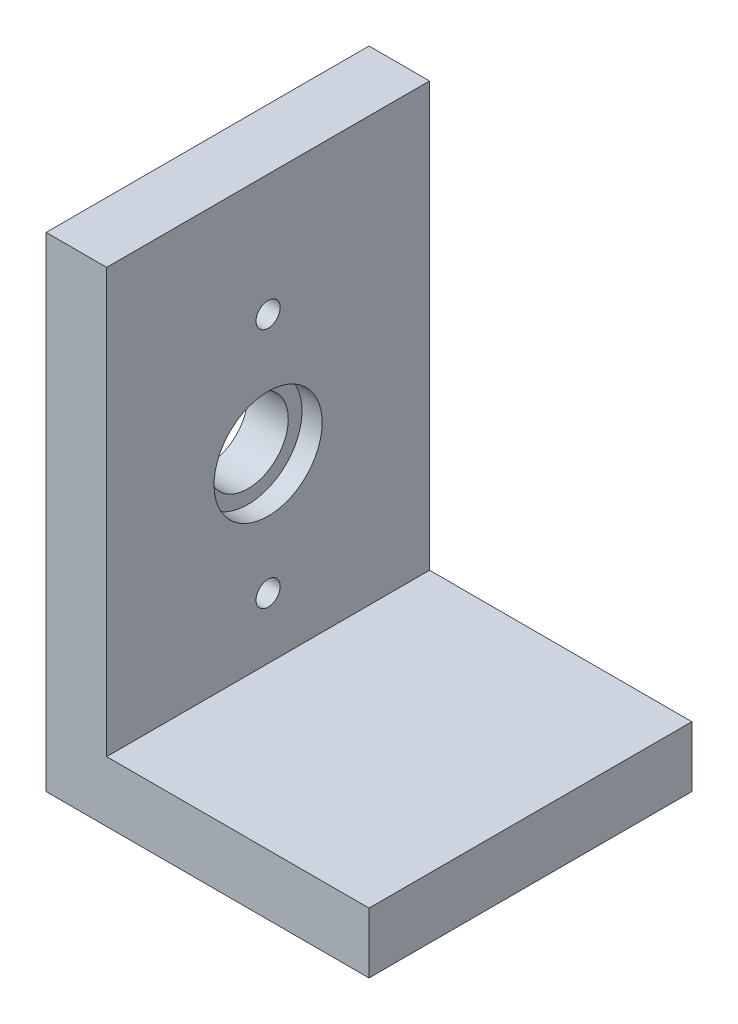
SolidWorks part; units mm, degrees
material "6061-T6 (SS)"
ref_plane "Front Plane" through (0, 0, 0) normal (0, 0, 1) x (1, 0, 0)
ref_plane "Top Plane" through (0, 0, 0) normal (0, 1, 0) x (1, 0, 0)
ref_plane "Right Plane" through (0, 0, 0) normal (1, 0, 0) x (0, 0, -1)
sketch "Sketch2" plane through (0, 0, 0) normal (0, 0, 1) x (1, 0, 0)
  line L0 (0, 0) -> (0, 76.2)
  line L1 (0, 76.2) -> (9.525, 76.2)
  line L2 (9.525, 76.2) -> (9.525, 9.525)
  line L3 (9.525, 9.525) -> (50.8, 9.525)
  line L4 (50.8, 9.525) -> (50.8, 0)
  line L5 (50.8, 0) -> (0, 0)
  dimension "D1" = 50.8
  dimension "D2" = 76.2
  dimension "D3" = 9.525
  dimension "D4" = 9.525
extrude "Boss-Extrude1" add sketch "Sketch2" along normal mid plane 50.8
sketch "Sketch5" plane through (9.525, 0, 0) normal (1, 0, 0) x (0, 0, -1)
  circle A0 centre (0, 38.1) radius 8.509
  point P2 (0, 0)
  dimension "D1" = 17.018
  dimension "D2" = 38.1
extrude "Cut-Extrude1" cut sketch "Sketch5" against normal blind 3.175
sketch "Sketch6" plane through (9.525, 0, 0) normal (1, 0, 0) x (0, 0, -1)
  circle A0 centre (0, 38.1) radius 8.509 construction
  circle A1 centre (0, 38.1) radius 8.509 construction
  circle A2 centre (0, 38.1) radius 6.35
  dimension "D1" = 12.7
extrude "Cut-Extrude2" cut sketch "Sketch6" against normal through all both and the other way through all
hole_wizard "#10-24 Tapped Hole1" positions "Sketch10" profile "Sketch9" tap size "#10-24" standard "ANSI Inch" end condition through all
sketch "Sketch10" plane through (9.525, 0, 0) normal (1, 0, 0) x (0, 0, -1)
  line L0 (0, 0) -> (0, 50000) construction
  line L1 (0, 38.1) -> (30.381, 38.1) construction
  circle A0 centre (0, 38.1) radius 8.509 construction
  circle A1 centre (0, 38.1) radius 8.509 construction
  point P0 (0, 57.0992)
  point P19 (0, 19.1008)
  point P23 (-18.9992, 38.1)
  point P24 (0, 0)
  point P25 (0, 56.3924)
  point P26 (0, 0)
  point P27 (0, 20.6778)
  dimension "D1" = 18.9992
  dimension "D2" = 18.9992
sketch "Sketch9" plane through (9.525, 57.0992, 0) normal (0, 1, 0) x (0, 0, -1)
  line L0 (0, 0) -> (0, 9.525)
  line L1 (0, 9.525) -> (1.8986, 9.525)
  line L2 (1.8986, 9.525) -> (1.8986, 0)
  line L5 (1.8986, 0) -> (0, 0)
  line L11 (0, -6.35) -> (0, 107.95) construction
  dimension "Thru Tap Drill Dia." = 3.7973
  dimension "Thru Tap Drill Depth" = 9.525
cosmetic thread "Hole Thread1" parameters "D2"=4.826
cosmetic thread "Hole Thread2" parameters "D2"=4.826
